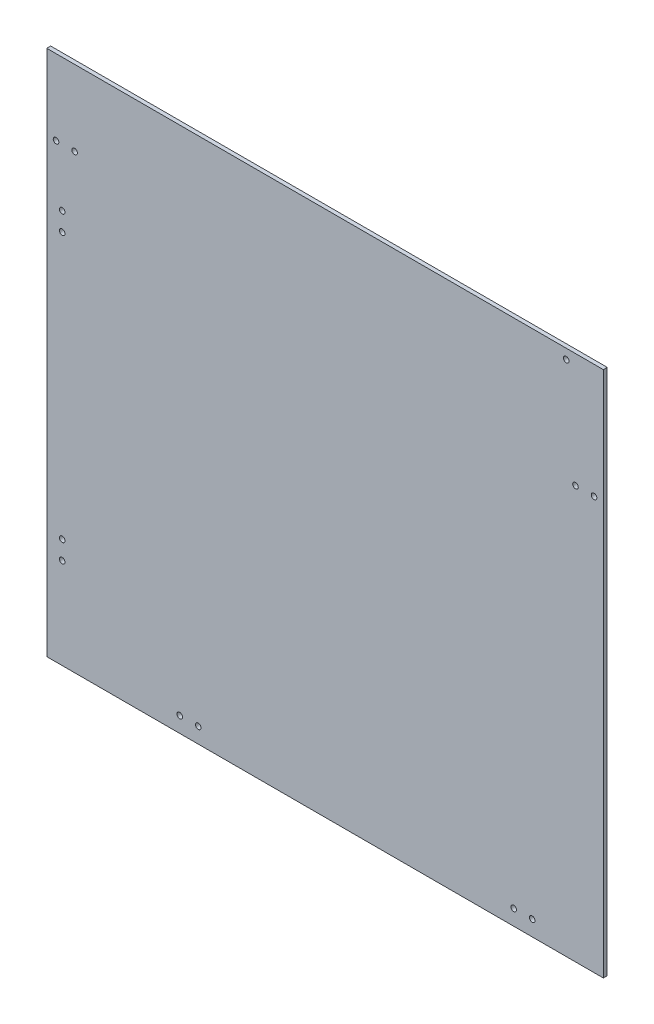
SolidWorks part; units mm, degrees
material "6061-O (SS)"
ref_plane "Front Plane" through (0, 0, 0) normal (0, 0, 1) x (1, 0, 0)
ref_plane "Top Plane" through (0, 0, 0) normal (0, 1, 0) x (1, 0, 0)
ref_plane "Right Plane" through (0, 0, 0) normal (1, 0, 0) x (0, 0, -1)
sketch "Sketch1" plane through (0, 0, 0) normal (0, 0, 1) x (1, 0, 0)
  line L1 (0, 0) -> (450, 0)
  line L2 (0, 0) -> (0, 426)
  line L3 (0, 426) -> (450, 426)
  line L4 (450, 0) -> (450, 426)
  dimension "D1" = 450
  dimension "D2" = 426
extrude "Boss-Extrude1" add sketch "Sketch1" along normal blind 3.175
sketch "Sketch8" plane through (0, 0, 0) normal (0, 0, -1) x (-1, 0, 0)
  line L0 (-450, 0) -> (-450, 426) construction
  line L1 (-450, 426) -> (0, 426) construction
  circle A0 centre (-420, 418) radius 2.25
  dimension "D3" = 4.5
  dimension "D1" = 30
  dimension "D2" = 8
extrude "Cut-Extrude7" cut sketch "Sketch8" against normal through all
sketch "Sketch2" plane through (0, 0, 3.175) normal (0, 0, 1) x (1, 0, 0)
  line L0 (450, 426) -> (0, 426) construction
  line L1 (450, 0) -> (450, 426) construction
  circle A0 centre (427.5, 333.5) radius 2.25
  circle A1 centre (442.5, 333.5) radius 2.25
  dimension "D4" = 4.5
  dimension "D1" = 92.5
  dimension "D2" = 15
  dimension "D3" = 7.5
extrude "Cut-Extrude1" cut sketch "Sketch2" against normal through all
sketch "Sketch3" plane through (0, 0, 3.175) normal (0, 0, 1) x (1, 0, 0)
  line L0 (450, 426) -> (0, 426) construction
  line L1 (0, 426) -> (0, 0) construction
  circle A0 centre (7.5, 365.055) radius 2.25
  circle A1 centre (22.5, 365.055) radius 2.25
  dimension "D4" = 4.5
  dimension "D1" = 60.945
  dimension "D2" = 15
  dimension "D3" = 7.5
extrude "Cut-Extrude2" cut sketch "Sketch3" against normal through all
sketch "Sketch4" [suppressed] plane through (0, 0, 0) normal (0, 0, -1) x (-1, 0, 0)
  line L0 (0, 426) -> (0, 0) construction
  circle A0 centre (-7.5, 352.175) radius 2.25
  circle A1 centre (-22.5, 352.175) radius 2.25
  dimension "D4" = 4.5
  dimension "D1" = 73.825
  dimension "D2" = 15
  dimension "D3" = 7.5
extrude "Cut-Extrude3" [suppressed] cut sketch "Sketch4" against normal through all
sketch "Sketch5" plane through (0, 0, 3.175) normal (0, 0, 1) x (1, 0, 0)
  line L0 (0, 0) -> (450, 0) construction
  line L1 (450, 0) -> (450, 426) construction
  line L2 (0, 426) -> (0, 0) construction
  circle A0 centre (377.5, 12.5) radius 2.25
  circle A1 centre (122.5, 12.5) radius 2.25
  circle A2 centre (107.5, 12.5) radius 2.25
  circle A3 centre (392.5, 12.5) radius 2.25
  dimension "D5" = 4.5
  dimension "D1" = 15
  dimension "D2" = 12.5
  dimension "D3" = 15
  dimension "D4" = 57.5
  dimension "D6" = 107.5
extrude "Cut-Extrude4" cut sketch "Sketch5" against normal through all
sketch "Sketch7" plane through (0, 0, 3.175) normal (0, 0, 1) x (1, 0, 0)
  line L0 (0, 426) -> (0, 0) construction
  line L1 (0, 0) -> (450, 0) construction
  circle A0 centre (12.5, 303.5) radius 2.25
  circle A1 centre (12.5, 318.5) radius 2.25
  circle A2 centre (12.5, 73.5) radius 2.25
  circle A3 centre (12.5, 88.5) radius 2.25
  dimension "D3" = 4.5
  dimension "D1" = 15
  dimension "D2" = 15
  dimension "D4" = 12.5
  dimension "D5" = 73.5
  dimension "D6" = 303.5
extrude "Cut-Extrude6" cut sketch "Sketch7" against normal through all
